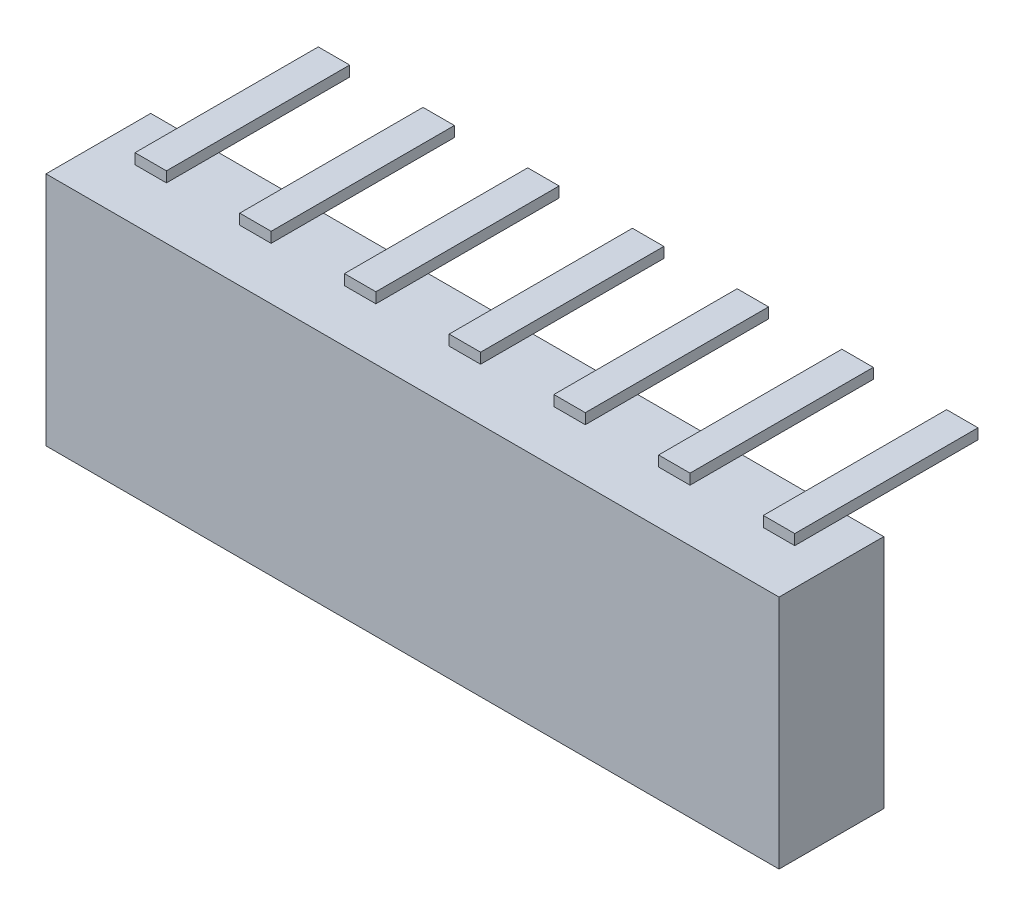
SolidWorks part; units mm, degrees
ref_plane "Front Plane" through (0, 0, 0) normal (0, 0, 1) x (1, 0, 0)
ref_plane "Top Plane" through (0, 0, 0) normal (0, 1, 0) x (1, 0, 0)
ref_plane "Right Plane" through (0, 0, 0) normal (1, 0, 0) x (0, 0, -1)
sketch "Sketch1" plane through (0, 0, 0) normal (0, 0, 1) x (1, 0, 0)
  line L1 (-1, 2.25) -> (1, 2.25)
  line L2 (-1, 2.25) -> (-1, -2.25)
  line L3 (-1, -2.25) -> (1, -2.25)
  line L4 (1, 2.25) -> (1, -2.25)
  line L5 (-1, 2.25) -> (1, -2.25) construction
  line L6 (-1, -2.25) -> (1, 2.25) construction
  point P0 (0, 0)
  dimension "D1" = 2
  dimension "D2" = 4.5
extrude "Boss-Extrude1" add sketch "Sketch1" along normal blind 2
sketch "Sketch2" plane through (0, -2.25, 0) normal (0, -1, 0) x (1, 0, 0)
  line L0 (0, 0) -> (0, 2) construction
  line L1 (-1, 2) -> (1, 2) construction
  line L9 (-0.4, 1.4) -> (0.4, 1.4)
  line L10 (-0.4, 1.4) -> (-0.4, 0.6)
  line L11 (-0.4, 0.6) -> (0.4, 0.6)
  line L12 (0.4, 1.4) -> (0.4, 0.6)
  line L13 (-0.4, 1.4) -> (0.4, 0.6) construction
  line L14 (-0.4, 0.6) -> (0.4, 1.4) construction
  point P10 (0, 1)
  dimension "D1" = 0.8
extrude "Cut-Extrude1" cut sketch "Sketch2" against normal blind 2.8
chamfer "Chamfer1" distance 0.2 angle 45 4 edges at (-0.4, -2.25, 1) (0, -2.25, 0.6) (0.4, -2.25, 1) (0, -2.25, 1.4)
sketch "Sketch3" plane through (0, 0, 0) normal (1, 0, 0) x (0, 0, -1)
  line L0 (-1, 2.25) -> (-1, 2.45)
  line L1 (-2, 2.25) -> (0, 2.25) construction
  line L2 (-1, 2.45) -> (2.5, 2.45)
  line L3 (2.5, 2.45) -> (2.5, 2.25)
  line L4 (2.5, 2.25) -> (-1, 2.25)
  line L5 (0, -2.25) -> (0, 2.25) construction
  dimension "D1" = 0.2
  dimension "D2" = 2.5
extrude "Boss-Extrude2" add sketch "Sketch3" along normal mid plane 0.6
pattern_linear "LPattern1" count 7 spacing 2 along (1, 0, 0) of "Boss-Extrude1", "Cut-Extrude1", "Chamfer1", "Boss-Extrude2"
